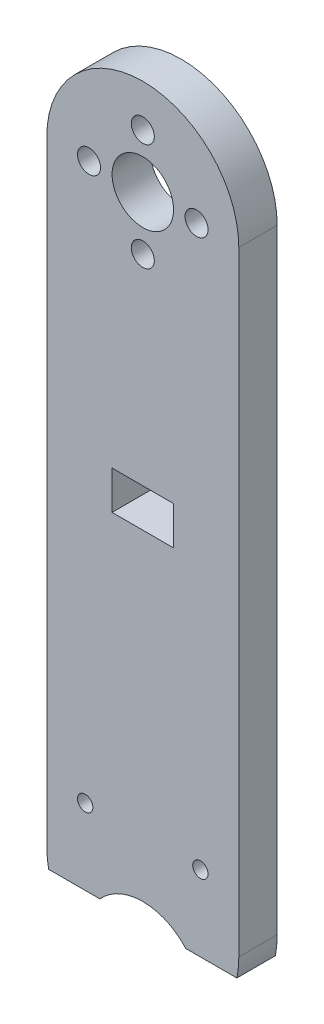
SolidWorks part; units mm, degrees
ref_plane "Front Plane" through (0, 0, 0) normal (0, 0, 1) x (1, 0, 0)
ref_plane "Top Plane" through (0, 0, 0) normal (0, 1, 0) x (1, 0, 0)
ref_plane "Right Plane" through (0, 0, 0) normal (1, 0, 0) x (0, 0, -1)
sketch "Sketch1" plane through (0, 0, 0) normal (0, 0, 1) x (1, 0, 0)
  line L0 (0, -40) -> (0, 40) construction
  line L1 (-12.5, -40) -> (-12.5, 40)
  line L2 (12.5, -40) -> (12.5, 40)
  line L3 (0, 40) -> (0, 52.5) construction
  line L4 (0, 40) -> (12.5, 40) construction
  line L5 (-12.5, -42.5) -> (12.5, -42.5)
  line L6 (0, -42.5) -> (0, -52.5) construction
  line L7 (-12.5, -42.5) -> (12.5, -42.5)
  line L8 (-12.5, -42.5) -> (-12.5, -52.5)
  line L9 (-12.5, -52.5) -> (12.5, -52.5)
  line L10 (12.5, -42.5) -> (12.5, -52.5)
  line L11 (-12.5, -30.05) -> (12.5, -30.05) construction
  arc A0 (-12.5, -40) -> (12.5, -40) centre (0, -40) ccw
  arc A1 (12.5, 40) -> (-12.5, 40) centre (0, 40) ccw
  circle A2 centre (0, 40) radius 4
  circle A3 centre (0, 47) radius 1.5
  circle A4 centre (7, 40) radius 1.5
  circle A5 centre (0, 33) radius 1.5
  circle A6 centre (-7, 40) radius 1.5
  circle A7 centre (0, -47.5) radius 7.5
  circle A9 centre (7.5, -32.65) radius 1
  circle A10 centre (-7.5, -32.65) radius 1
  point P2 (0, 0)
  point P8 (0, 52.5)
  point P9 (0, -52.5)
  dimension "D3" = 8
  dimension "D4" = 3
  dimension "D5" = 7
  dimension "D6" = 3
  dimension "D10" = 15
  dimension "D12" = 2
  dimension "D14" = 7.5
  dimension "D1" = 25
  dimension "D2" = 105
  dimension "D7" = 7
  dimension "D8" = 10
  dimension "D9" = 10
  dimension "D11" = 12.45
  dimension "D13" = 2.6
extrude "Boss-Extrude2" add sketch "Sketch1" along normal blind 5 contours A7 L7 A0 L2 A1 L1 A5 A4 A3 A2 A6
ref_plane "Plane1" through (0, 0, 6) normal (0, 0, 1) x (1, 0, 0)
sketch "Sketch2" plane through (0, 0, 6) normal (0, 0, 1) x (1, 0, 0)
  line L0 (0, 31.5) -> (0, 4.38) construction
  line L2 (-4, 6.88) -> (4, 6.88)
  line L3 (-4, 6.88) -> (-4, 1.88)
  line L4 (-4, 1.88) -> (4, 1.88)
  line L5 (4, 6.88) -> (4, 1.88)
  line L6 (-4, 6.88) -> (4, 1.88) construction
  line L7 (-4, 1.88) -> (4, 6.88) construction
  circle A0 centre (0, 33) radius 1.5 construction
  dimension "D1" = 27.12
  dimension "D2" = 8
  dimension "D3" = 5
extrude "Cut-Extrude1" cut sketch "Sketch2" against normal blind 10
